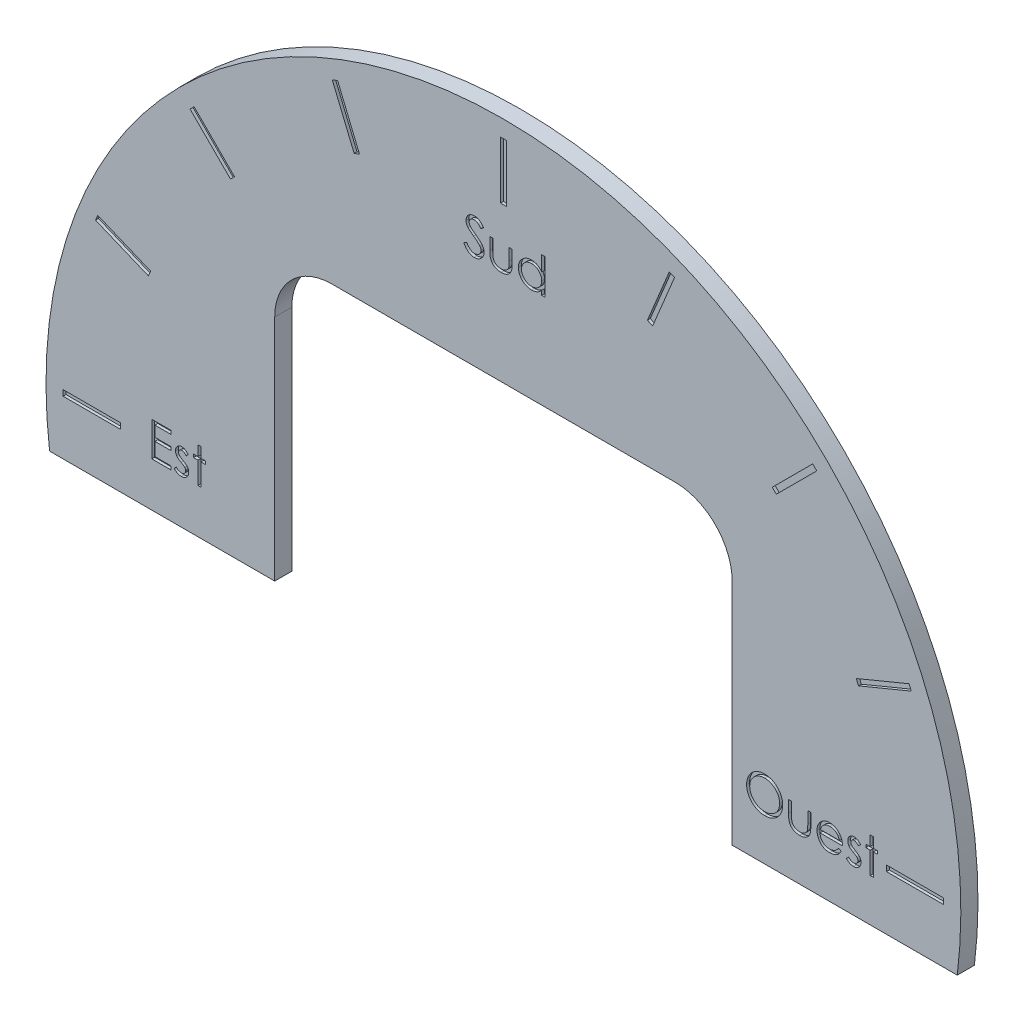
SolidWorks part; units mm, degrees
ref_plane "Plan de face" through (0, 0, 0) normal (0, 0, 1) x (1, 0, 0)
ref_plane "Plan de dessus" through (0, 0, 0) normal (0, 1, 0) x (1, 0, 0)
ref_plane "Plan de droite" through (0, 0, 0) normal (1, 0, 0) x (0, 0, -1)
sketch "Esquisse1" plane through (0, 0, 0) normal (0, 0, 1) x (1, 0, 0)
  line L0 (-79.3725, -10) -> (-40, -10)
  line L1 (-30, 40) -> (30, 40)
  line L2 (-40, 30) -> (-40, -10)
  line L4 (40, 30) -> (40, -10)
  line L8 (40, -10) -> (79.3725, -10)
  arc A0 (79.3725, -10) -> (-79.3725, -10) centre (0, 0) ccw
  arc A1 (30, 40) -> (40, 30) centre (30, 30) cw
  arc A2 (-30, 40) -> (-40, 30) centre (-30, 30) ccw
  point P7 (40, 40)
  point P12 (-40, 40)
  dimension "D1" = 160
  dimension "D2" = 10
  dimension "D3" = 80
  dimension "D4" = 10
extrude "Boss.-Extru.1" add sketch "Esquisse1" along normal blind 3
sketch "Esquisse2" plane through (0, 0, 3) normal (0, 0, 1) x (1, 0, 0)
  line L0 (0, 0) -> (-72, 0) construction
  line L1 (-61.7086, 26.1017) -> (-62.0913, 25.1779)
  line L2 (-77, 0.5) -> (-67, 0.5)
  line L3 (-77, 0.5) -> (-77, -0.5)
  line L4 (-77, -0.5) -> (-67, -0.5)
  line L5 (-67, 0.5) -> (-67, -0.5)
  line L6 (-77, 0.5) -> (-67, -0.5) construction
  line L7 (-77, -0.5) -> (-67, 0.5) construction
  line L8 (-70.9474, 29.9286) -> (-61.7086, 26.1017)
  line L9 (-71.3301, 29.0047) -> (-62.0913, 25.1779)
  line L10 (-70.9474, 29.9286) -> (-71.3301, 29.0047)
  line L11 (-47.0226, 47.7297) -> (-47.7297, 47.0226)
  line L12 (-54.0937, 54.8008) -> (-47.0226, 47.7297)
  line L13 (-54.8008, 54.0937) -> (-47.7297, 47.0226)
  line L14 (-54.0937, 54.8008) -> (-54.8008, 54.0937)
  line L15 (-25.1779, 62.0913) -> (-26.1017, 61.7086)
  line L16 (-29.0047, 71.3301) -> (-25.1779, 62.0913)
  line L17 (-29.9286, 70.9474) -> (-26.1017, 61.7086)
  line L18 (-29.0047, 71.3301) -> (-29.9286, 70.9474)
  line L19 (0.5, 67) -> (-0.5, 67)
  line L20 (0.5, 77) -> (0.5, 67)
  line L21 (-0.5, 77) -> (-0.5, 67)
  line L22 (0.5, 77) -> (-0.5, 77)
  line L23 (26.1017, 61.7086) -> (25.1779, 62.0913)
  line L24 (29.9286, 70.9474) -> (26.1017, 61.7086)
  line L25 (29.0047, 71.3301) -> (25.1779, 62.0913)
  line L26 (29.9286, 70.9474) -> (29.0047, 71.3301)
  line L27 (47.7297, 47.0226) -> (47.0226, 47.7297)
  line L28 (54.8008, 54.0937) -> (47.7297, 47.0226)
  line L29 (54.0937, 54.8008) -> (47.0226, 47.7297)
  line L30 (54.8008, 54.0937) -> (54.0937, 54.8008)
  line L31 (62.0913, 25.1779) -> (61.7086, 26.1017)
  line L32 (71.3301, 29.0047) -> (62.0913, 25.1779)
  line L33 (70.9474, 29.9286) -> (61.7086, 26.1017)
  line L34 (71.3301, 29.0047) -> (70.9474, 29.9286)
  line L35 (67, -0.5) -> (67, 0.5)
  line L36 (77, -0.5) -> (67, -0.5)
  line L37 (77, 0.5) -> (67, 0.5)
  line L38 (77, -0.5) -> (77, 0.5)
  point P41 (0, 0)
  dimension "D1" = 72
  dimension "D2" = 10
  dimension "D3" = 1
  dimension "D4" = 9
extrude "Enlèv. mat.-Extru.1" cut sketch "Esquisse2" against normal blind 0.5
sketch "Esquisse3" plane through (0, 0, 3) normal (0, 0, 1) x (1, 0, 0)
  text T0 "Est" font "Century Gothic" height 6
  text T1 "Ouest" font "Century Gothic" height 6
  text T2 "Sud" font "Century Gothic" height 6
  point P2 (45.0186, 0)
  point P3 (0, 0)
  point P4 (0, 0)
  point P5 (0, 0)
  point P6 (0, 0)
  point P7 (0, 0)
  point P8 (0, 0)
  point P9 (0, 0)
extrude "Enlèv. mat.-Extru.2" cut sketch "Esquisse3" against normal blind 0.5
